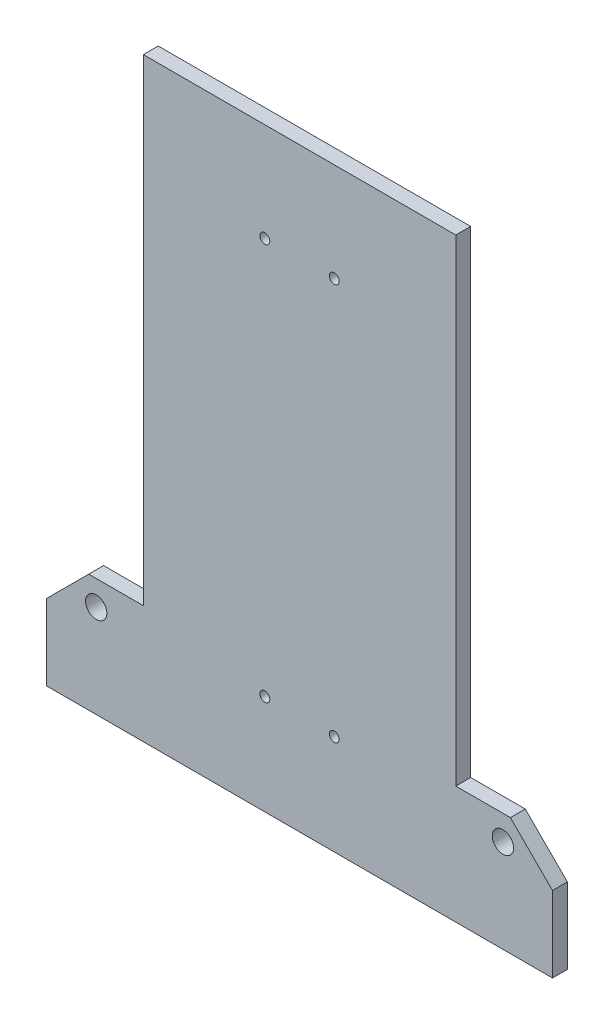
SolidWorks part; units mm, degrees
material "ABS"
ref_plane "前视基准面" through (0, 0, 0) normal (0, 0, 1) x (1, 0, 0)
ref_plane "上视基准面" through (0, 0, 0) normal (0, 1, 0) x (1, 0, 0)
ref_plane "右视基准面" through (0, 0, 0) normal (1, 0, 0) x (0, 0, -1)
sketch "草图1" plane through (0, 0, 0) normal (0, 0, 1) x (1, 0, 0)
  line L0 (-51.0025, -68.8919) -> (51.0025, -68.8919)
  line L1 (-51.0025, -141.1287) -> (-51.0025, -53.6128) construction
  line L2 (51.0025, -53.6128) -> (51.0025, -141.1287) construction
  line L3 (51.0025, -68.8919) -> (51.0025, 35.2667)
  line L5 (51.0025, 35.2667) -> (40.1096, 51.1081)
  line L6 (40.1096, 51.1081) -> (-37.0964, 51.1081)
  line L7 (-37.0964, 51.1081) -> (-51.0025, 41.546)
  line L8 (-51.0025, 41.546) -> (-51.0025, -68.8919)
  line L9 (53.9975, -68.8919) -> (-54.0025, -68.8919) construction
  point P9 (0, 0)
  point P16 (0, 0)
  point P17 (0, 0)
  point P18 (0, 0)
  point P19 (4.6711, 51.1081)
  point P20 (-5.2658, 51.1081)
  point P21 (51.0025, 35.2667)
  point P22 (-51.0025, 41.546)
  dimension "D1" = 120
extrude "凸台-拉伸1" add sketch "草图1" against normal blind 3
sketch "草图2" plane through (0, 0, 0) normal (0, 0, 1) x (1, 0, 0)
  circle A0 centre (-41.0025, 9.8725) radius 2.15
  circle A1 centre (-41.0025, -50.1275) radius 2.15
  circle A2 centre (41.0025, 9.8725) radius 2.15
  circle A3 centre (41.0025, -50.1275) radius 2.15
  point P12 (0, 0)
  point P13 (0, 0)
extrude "切除-拉伸1" cut sketch "草图2" against normal blind 3
sketch "草图3" plane through (0, 0, -3) normal (0, 0, -1) x (-1, 0, 0)
  circle A0 centre (-7.0002, 31.25) radius 1
  circle A1 centre (6.9998, 31.25) radius 1
  circle A2 centre (-7.0002, -48.75) radius 1
  circle A3 centre (6.9998, -48.75) radius 1
extrude "切除-拉伸2" cut sketch "草图3" against normal blind 70
sketch "Sketch1" plane through (0, 0, 0) normal (0, 0, 1) x (1, 0, 0)
  line L0 (51.0025, -53.6128) -> (42.5172, -45.1275) construction
  line L1 (42.5172, -45.1275) -> (26.0025, -45.1275) construction
  line L2 (-26.0025, -45.1275) -> (-42.5172, -45.1275) construction
  line L3 (-42.5172, -45.1275) -> (-51.0025, -53.6128) construction
  line L4 (51.0025, -53.6128) -> (42.5172, -45.1275)
  line L5 (42.5172, -45.1275) -> (31.5, -45.1275)
  line L6 (-31.5, -45.1275) -> (-42.5172, -45.1275)
  line L7 (-42.5172, -45.1275) -> (-51.0025, -53.6128)
  line L8 (-31.5, 54.9564) -> (-31.5, -45.1275)
  line L9 (-31.5, -46.8213) -> (-31.5, 52.4522) construction
  line L10 (-37.0964, 51.1081) -> (-51.0025, 41.546) construction
  line L11 (31.5, 63.6291) -> (31.5, -45.1275)
  line L12 (31.5, 52.4522) -> (31.5, -46.8213) construction
  line L13 (51.0025, 35.2667) -> (40.1096, 51.1081) construction
  line L14 (-31.5, 54.9564) -> (-51.0025, 54.9564)
  line L15 (-51.0025, 54.9564) -> (-51.0025, -53.6128)
  line L16 (31.5, 63.6291) -> (51.0025, 63.6291)
  line L17 (51.0025, 63.6291) -> (51.0025, -53.6128)
extrude "Cut-Extrude1" cut sketch "Sketch1" against normal blind 10
